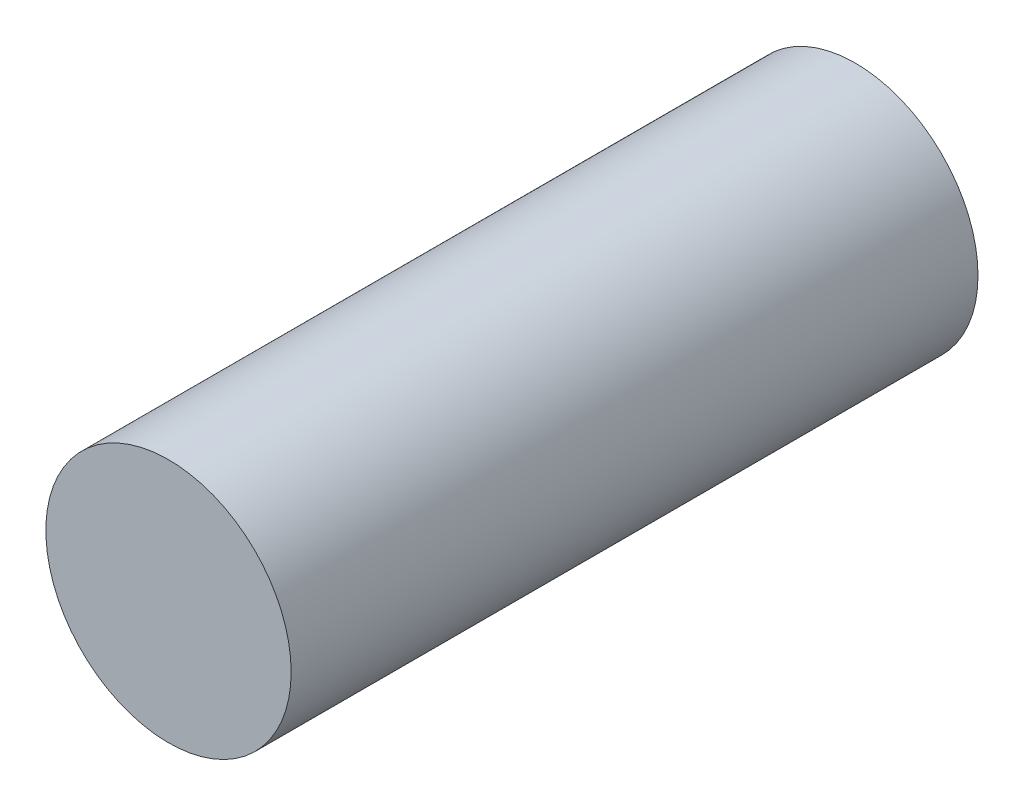
SolidWorks part; units mm, degrees
ref_plane "Спереди" through (0, 0, 0) normal (0, 0, 1) x (1, 0, 0)
ref_plane "Сверху" through (0, 0, 0) normal (0, 1, 0) x (1, 0, 0)
ref_plane "Справа" through (0, 0, 0) normal (1, 0, 0) x (0, 0, -1)
sketch "Эскиз1" plane through (0, 0, 0) normal (0, 0, 1) x (1, 0, 0)
  circle A0 centre (0, 0) radius 2.5
  dimension "D1" = 5
extrude "Бобышка-Вытянуть1" add sketch "Эскиз1" along normal blind 14
